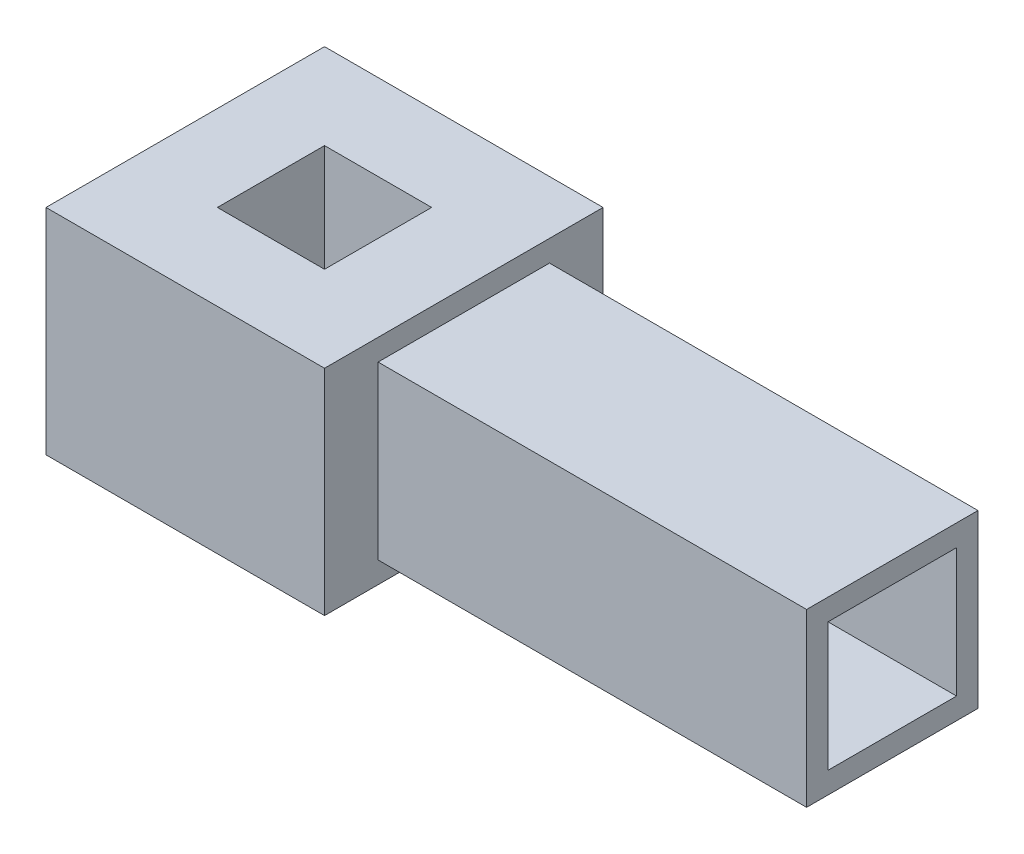
SolidWorks part; units mm, degrees
ref_plane "Front Plane" through (0, 0, 0) normal (0, 0, 1) x (1, 0, 0)
ref_plane "Top Plane" through (0, 0, 0) normal (0, 1, 0) x (1, 0, 0)
ref_plane "Right Plane" through (0, 0, 0) normal (1, 0, 0) x (0, 0, -1)
sketch "Sketch1" plane through (0, 0, 0) normal (0, 1, 0) x (1, 0, 0)
  line L0 (-32.5, 32.5) -> (-32.5, -32.5)
  line L1 (-12.5, 12.5) -> (12.5, 12.5)
  line L2 (-12.5, 12.5) -> (-12.5, -12.5)
  line L3 (-12.5, -12.5) -> (12.5, -12.5)
  line L4 (12.5, 12.5) -> (12.5, -12.5)
  line L5 (-12.5, 12.5) -> (12.5, -12.5) construction
  line L6 (-12.5, -12.5) -> (12.5, 12.5) construction
  line L7 (-32.5, -32.5) -> (32.5, -32.5)
  line L8 (32.5, 32.5) -> (32.5, -32.5)
  line L9 (-32.5, 32.5) -> (32.5, 32.5)
  point P0 (0, 0)
  dimension "D1" = 25
  dimension "D2" = 25
  dimension "D3" = 20
extrude "Boss-Extrude1" add sketch "Sketch1" along normal blind 50
sketch "Sketch2" plane through (32.5, 0, 0) normal (1, 0, 0) x (0, 0, -1)
  line L0 (-32.5, 50) -> (32.5, 0) construction
  line L1 (-32.5, 0) -> (32.5, 50) construction
  line L2 (-15, 40) -> (15, 40)
  line L3 (-20, 45) -> (20, 45)
  line L4 (-20, 45) -> (-20, 5)
  line L5 (-20, 5) -> (20, 5)
  line L6 (20, 45) -> (20, 5)
  line L7 (-20, 45) -> (20, 5) construction
  line L8 (-20, 5) -> (20, 45) construction
  line L9 (15, 40) -> (15, 10)
  line L10 (-15, 10) -> (15, 10)
  line L11 (-15, 40) -> (-15, 10)
  point P8 (0, 25)
  dimension "D1" = 40
  dimension "D2" = 40
  dimension "D3" = 5
extrude "Boss-Extrude2" add sketch "Sketch2" along normal blind 100
